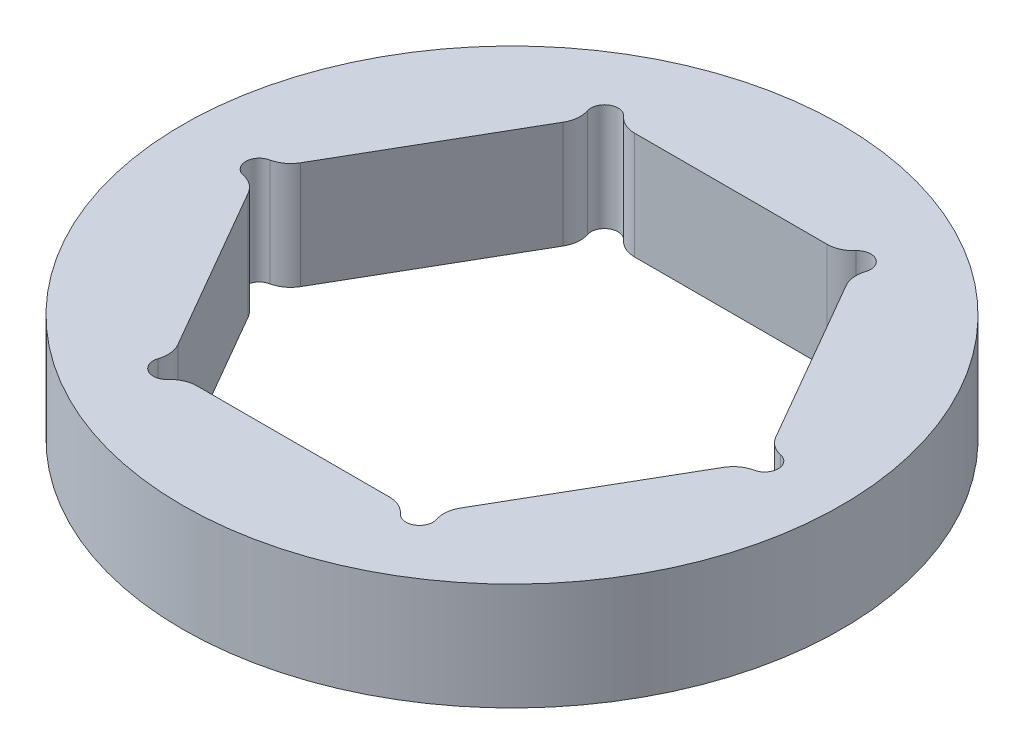
SolidWorks part; units mm, degrees
material "ABS"
ref_plane "Alzado" through (0, 0, 0) normal (0, 0, 1) x (1, 0, 0)
ref_plane "Planta" through (0, 0, 0) normal (0, 1, 0) x (1, 0, 0)
ref_plane "Vista lateral" through (0, 0, 0) normal (1, 0, 0) x (0, 0, -1)
sketch "Croquis1" plane through (0, 0, 0) normal (0, 1, 0) x (1, 0, 0)
  line L1 (4.1867, -5.7024) -> (7.0318, -0.7746)
  line L2 (7.0318, 0.7746) -> (4.1867, 5.7024)
  line L3 (2.8451, 6.477) -> (-2.8451, 6.477)
  line L4 (-4.1867, 5.7024) -> (-7.0318, 0.7746)
  line L5 (-7.0318, -0.7746) -> (-4.1867, -5.7024)
  line L6 (-2.8451, -6.477) -> (2.8451, -6.477)
  circle A0 centre (0, 0) radius 9.7536
  circle A1 centre (0, 0) radius 6.477 construction
  arc A2 (-3.4414, 6.7437) -> (-4.1195, 6.3521) centre (-3.7395, 6.477) ccw
  arc A3 (-3.4414, 6.7437) -> (-2.8451, 6.477) centre (-2.8451, 7.277) ccw
  arc A4 (-4.1867, 5.7024) -> (-4.1195, 6.3521) centre (-4.8795, 6.1024) ccw
  arc A5 (4.1195, 6.3521) -> (3.4414, 6.7437) centre (3.7395, 6.477) ccw
  arc A6 (4.1195, 6.3521) -> (4.1867, 5.7024) centre (4.8795, 6.1024) ccw
  arc A7 (2.8451, 6.477) -> (3.4414, 6.7437) centre (2.8451, 7.277) ccw
  arc A8 (7.5609, -0.3915) -> (7.5609, 0.3915) centre (7.479, 0) ccw
  arc A9 (7.5609, -0.3915) -> (7.0318, -0.7746) centre (7.7246, -1.1746) ccw
  arc A10 (7.0318, 0.7746) -> (7.5609, 0.3915) centre (7.7246, 1.1746) ccw
  arc A11 (3.4414, -6.7437) -> (4.1195, -6.3521) centre (3.7395, -6.477) ccw
  arc A12 (3.4414, -6.7437) -> (2.8451, -6.477) centre (2.8451, -7.277) ccw
  arc A13 (4.1867, -5.7024) -> (4.1195, -6.3521) centre (4.8795, -6.1024) ccw
  arc A14 (-4.1195, -6.3521) -> (-3.4414, -6.7437) centre (-3.7395, -6.477) ccw
  arc A15 (-4.1195, -6.3521) -> (-4.1867, -5.7024) centre (-4.8795, -6.1024) ccw
  arc A16 (-2.8451, -6.477) -> (-3.4414, -6.7437) centre (-2.8451, -7.277) ccw
  arc A17 (-7.5609, 0.3915) -> (-7.5609, -0.3915) centre (-7.479, 0) ccw
  arc A18 (-7.5609, 0.3915) -> (-7.0318, 0.7746) centre (-7.7246, 1.1746) ccw
  arc A19 (-7.0318, -0.7746) -> (-7.5609, -0.3915) centre (-7.7246, -1.1746) ccw
  dimension "D2" = 19.5072
  dimension "D3" = 0.8
  dimension "D4" = 0.8
  dimension "D1" = 12.954
  dimension "D5" = 6
extrude "Saliente-Extruir1" add sketch "Croquis1" along normal mid plane 3.175
